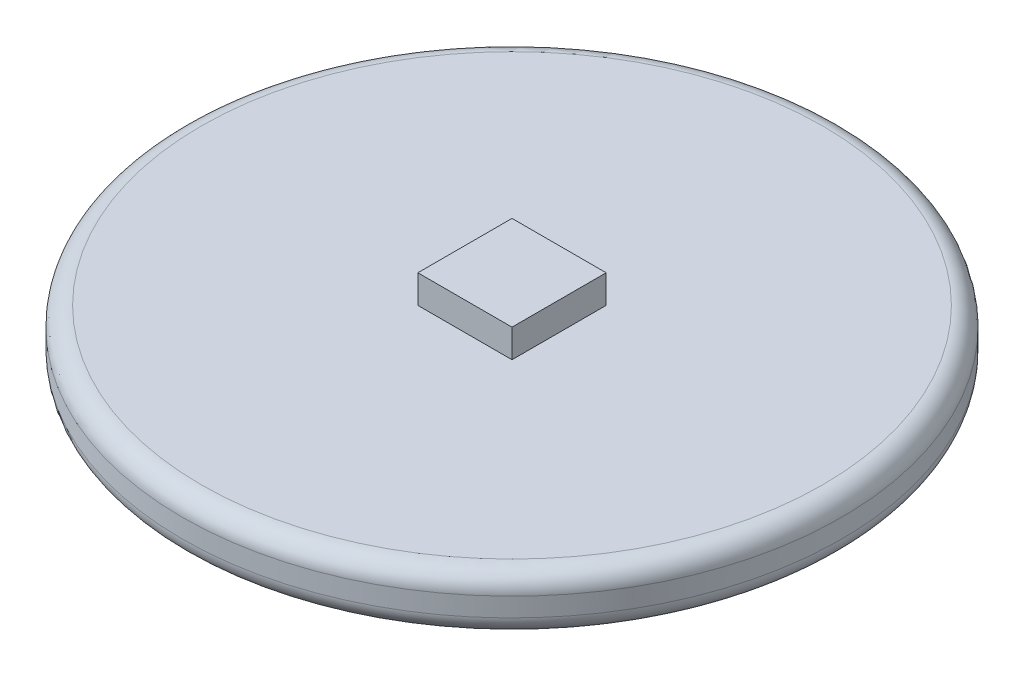
SolidWorks part; units mm, degrees
ref_plane "Front Plane" through (0, 0, 0) normal (0, 0, 1) x (1, 0, 0)
ref_plane "Top Plane" through (0, 0, 0) normal (0, 1, 0) x (1, 0, 0)
ref_plane "Right Plane" through (0, 0, 0) normal (1, 0, 0) x (0, 0, -1)
sketch "Sketch1" plane through (0, 0, 0) normal (0, 1, 0) x (1, 0, 0)
  circle A0 centre (0, 0) radius 35
  dimension "D1" = 70
extrude "Boss-Extrude1" add sketch "Sketch1" along normal blind 6
fillet "Fillet2" radius 2 2 edges at (0, 0, 35) (0, 6, 35)
sketch "Sketch3" plane through (0, 6, 0) normal (0, 1, 0) x (1, 0, 0)
  line L1 (5, -5) -> (-5, -5)
  line L2 (5, -5) -> (5, 5)
  line L3 (5, 5) -> (-5, 5)
  line L4 (-5, -5) -> (-5, 5)
  line L5 (5, -5) -> (-5, 5) construction
  line L6 (5, 5) -> (-5, -5) construction
  point P0 (0, 0)
  dimension "D1" = 10
  dimension "D2" = 10
extrude "Boss-Extrude3" add sketch "Sketch3" along normal blind 3
